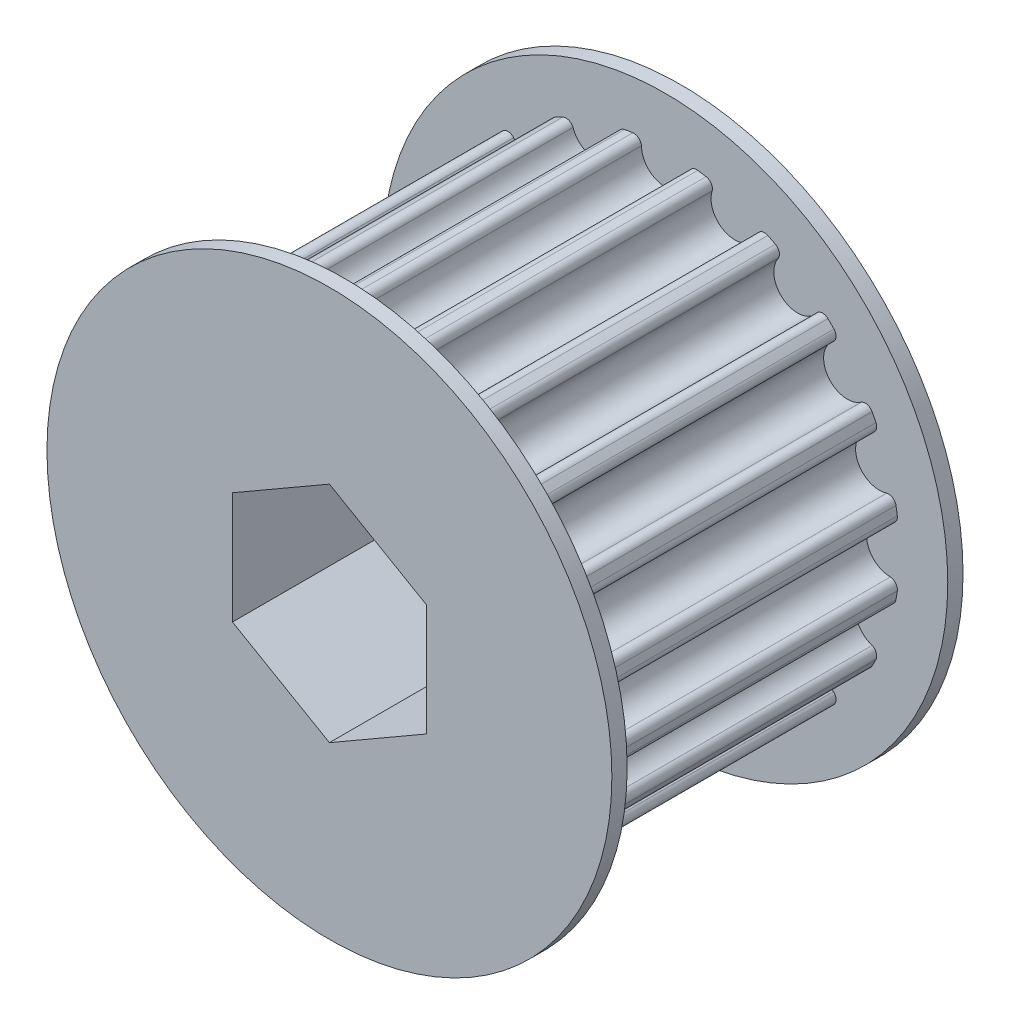
SolidWorks part; units mm, degrees
material "6061-T6 (SS)"
ref_plane "Front Plane" through (0, 0, 0) normal (0, 0, 1) x (1, 0, 0)
ref_plane "Top Plane" through (0, 0, 0) normal (0, 1, 0) x (1, 0, 0)
ref_plane "Right Plane" through (0, 0, 0) normal (1, 0, 0) x (0, 0, -1)
sketch "Pitch diameter" plane through (0, 0, 0) normal (0, 0, 1) x (1, 0, 0)
  circle A0 centre (0, 0) radius 15.9155 construction
  dimension "D1" = 31.831
sketch "Sketch2" plane through (0, 0, 0) normal (0, 0, 1) x (1, 0, 0)
  circle A0 centre (0, 0) radius 15.344
  dimension "D1" = 30.688
extrude "Boss-Extrude1" add sketch "Sketch2" along normal blind 21
sketch "Sketch3" plane through (0, 0, 0) normal (0, 0, -1) x (-1, 0, 0)
  line L0 (-1.6145, 15.2588) -> (-1.56, 14.744)
  line L1 (1.6145, 15.2588) -> (1.56, 14.744)
  line L2 (-1.56, 14.744) -> (1.56, 14.744) construction
  circle A0 centre (0, 0) radius 15.344 construction
  arc A1 (-1.56, 14.744) -> (1.56, 14.744) centre (0, 14.744) ccw
  circle A2 centre (0, 0) radius 15.344 construction
  arc A3 (1.6145, 15.2588) -> (-1.6145, 15.2588) centre (0, 0) ccw
  point P10 (0, 14.744)
  point P15 (0, 13.184)
  point P16 (0, 15.344)
  dimension "D1" = 1.56
  dimension "D2" = 2.16
extrude "Cut-Extrude1" cut sketch "Sketch3" against normal through all
fillet "Fillet1" radius 0.5 2 edges at (-1.6145, 15.2588, 10.5) (1.6145, 15.2588, 10.5)
pattern_circular "CirPattern1" count 20 over 360 about axis through (0, 0, 0) along (0, 0, 1) of "Cut-Extrude1", "Fillet1"
sketch "Sketch5" plane through (0, 0, 0) normal (0, 0, -1) x (-1, 0, 0)
  line L1 (0, -7.3323) -> (6.35, -3.6662)
  line L2 (6.35, -3.6662) -> (6.35, 3.6662)
  line L3 (6.35, 3.6662) -> (0, 7.3323)
  line L4 (0, 7.3323) -> (-6.35, 3.6662)
  line L5 (-6.35, 3.6662) -> (-6.35, -3.6662)
  line L6 (-6.35, -3.6662) -> (0, -7.3323)
  circle A1 centre (0, 0) radius 6.35 construction
  dimension "D1" = 12.7
  dimension "D2" = 12.7
extrude "Cut-Extrude2" cut sketch "Sketch5" against normal through all
ref_plane "Plane1" through (0, 0, 10.5) normal (0, 0, 1) x (1, 0, 0)
sketch "Sketch7" plane through (0, 0, 21) normal (0, 0, 1) x (1, 0, 0)
  line L0 (6.35, -3.6662) -> (0, -7.3323) construction
  line L1 (0, -7.3323) -> (-6.35, -3.6662) construction
  line L2 (-6.35, -3.6662) -> (-6.35, 3.6662) construction
  line L3 (-6.35, 3.6662) -> (0, 7.3323) construction
  line L4 (0, 7.3323) -> (6.35, 3.6662) construction
  line L5 (6.35, 3.6662) -> (6.35, -3.6662) construction
  line L6 (6.35, -3.6662) -> (0, -7.3323)
  line L7 (0, -7.3323) -> (-6.35, -3.6662)
  line L8 (-6.35, -3.6662) -> (-6.35, 3.6662)
  line L9 (-6.35, 3.6662) -> (0, 7.3323)
  line L10 (0, 7.3323) -> (6.35, 3.6662)
  line L11 (6.35, 3.6662) -> (6.35, -3.6662)
  circle A0 centre (0, 0) radius 18.5
  dimension "D1" = 37
extrude "Boss-Extrude2" add sketch "Sketch7" along normal blind 1
mirror "Mirror1" about plane through (0, 0, 10.5) normal (0, 0, 1) of "Boss-Extrude2"
equation "\"NumberOfTeeth\"= 20"
equation "\"Pitch\"= 5mm"
equation "\"PitchDiameter\"= ( \"Pitch\" * \"NumberOfTeeth\" ) / Pi"
equation "\"OD\"= \"PitchDiameter\" - 0.0225in * 2"
equation "\"D1@Pitch diameter\" = \"PitchDiameter\""
equation "\"D1@Sketch2\"=\"OD\""
equation "\"D1@CirPattern1\"=\"NumberOfTeeth\""
